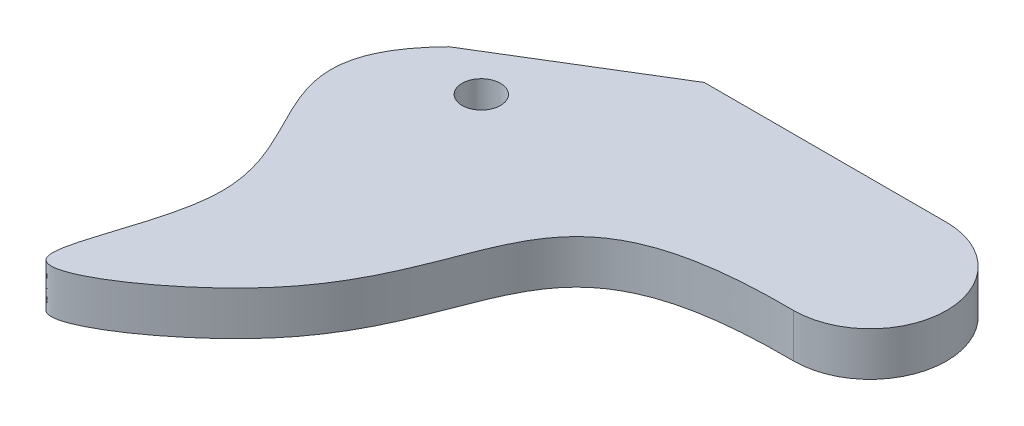
SolidWorks part; units mm, degrees
ref_plane "Front Plane" through (0, 0, 0) normal (0, 0, 1) x (1, 0, 0)
ref_plane "Top Plane" through (0, 0, 0) normal (0, 1, 0) x (1, 0, 0)
ref_plane "Right Plane" through (0, 0, 0) normal (1, 0, 0) x (0, 0, -1)
sketch "Sketch1" plane through (0, 0, 0) normal (0, 1, 0) x (1, 0, 0)
  line L0 (-13.2289, 8.0355) -> (11.653, 8.0355)
  line L1 (-13.2289, 8.0355) -> (-29.5278, -1.9054)
  circle A0 centre (-23.6206, -4.479) radius 1.975
  arc A1 (11.653, -7.6601) -> (11.653, 8.0355) centre (11.653, 0.1877) ccw
  spline S0 degree 3 poles (-29.5278, -1.9054) (-39.3739, -12.0427) (-21.4838, -19.6225) (-37.0612, -48.0942) (-2.779, -24.806) (-14.139, -7.3734) (11.653, -7.6601) knots 0 0 0 0 0.264966 0.418851 0.587126 1 1 1 1
  dimension "D1" = 3.95
extrude "Boss-Extrude1" add sketch "Sketch1" along normal blind 4.5
